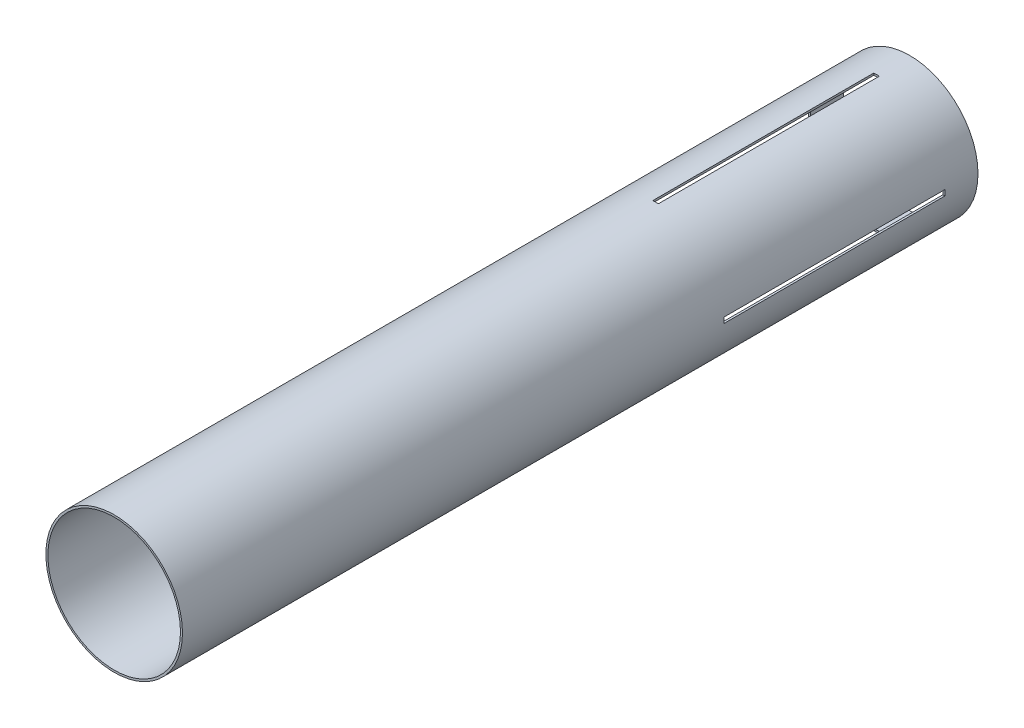
SolidWorks part; units mm, degrees
ref_plane "Front Plane" through (0, 0, 0) normal (0, 0, 1) x (1, 0, 0)
ref_plane "Top Plane" through (0, 0, 0) normal (0, 1, 0) x (1, 0, 0)
ref_plane "Right Plane" through (0, 0, 0) normal (1, 0, 0) x (0, 0, -1)
sketch "Sketch1" plane through (0, 0, 0) normal (0, 0, 1) x (1, 0, 0)
  circle A0 centre (0, 0) radius 39.2557
  circle A1 centre (0, 0) radius 38.1
  dimension "D1" = 76.2
  dimension "D2" = 78.5114
extrude "Boss-Extrude1" add sketch "Sketch1" along normal mid plane 457.2
sketch "Sketch3" plane through (0, 0, 0) normal (0, 1, 0) x (1, 0, 0)
  line L0 (39.2557, 228.6) -> (-39.2557, 228.6) construction
  line L1 (1.5875, 82.55) -> (-1.5875, 82.55)
  line L2 (1.5875, 82.55) -> (1.5875, 209.55)
  line L3 (1.5875, 209.55) -> (-1.5875, 209.55)
  line L4 (-1.5875, 82.55) -> (-1.5875, 209.55)
  line L5 (1.5875, 82.55) -> (-1.5875, 209.55) construction
  line L6 (1.5875, 209.55) -> (-1.5875, 82.55) construction
  line L7 (39.2557, 228.6) -> (-39.2557, 228.6) construction
  point P0 (0, 146.05)
  point P7 (0, 0)
  dimension "D1" = 3.175
  dimension "D2" = 127
  dimension "D3" = 19.05
extrude "Cut-Extrude1" cut sketch "Sketch3" along normal through all
pattern_circular "CirPattern1" count 4 over 360 about axis through (0, 0, 0) along (0, 0, 1) of "Cut-Extrude1"
equation "\"AIRFRAME_OD\"= 3.091in"
equation "\"AIRFRAME_ID\"= 3.00in"
equation "\"FLAT_T\" = 0.125in"
equation "\"NOSE_EXP_L\"= 3.5in"
equation "\"NOSE_SHOULDER_L\" = 5in"
equation "\"MAIN_L\" = 18in"
equation "\"RECO_COUP_L\" = 6in"
equation "\"RECO_SWITCH_L\" = 1.5in"
equation "\"DROGUE_L\" = 14in"
equation "\"ATS_FORE_COUP_L\" = 4in"
equation "\"ATS_AFT_COUP_L\" = 4in"
equation "\"LOWER_L\" = 18in"
equation "\"FIN_N\" = 4"
equation "\"CR_AFT_X\" = 0.5in"
equation "\"CR_FORE_X\" = 6in"
equation "\"D1@Sketch1\"=\"AIRFRAME_ID\""
equation "\"D2@Sketch1\"=\"AIRFRAME_OD\""
equation "\"D1@Boss-Extrude1\"=\"LOWER_L\""
equation "\"FIN_ROOT\" = 5in"
equation "\"FIN_X\" = 0.75in"
equation "\"MOTOR_OD\" = 2.25in"
equation "\"MOTOR_ID\" = 2.126in"
equation "\"D1@Sketch3\"=\"FLAT_T\""
equation "\"D2@Sketch3\"=\"FIN_ROOT\""
equation "\"D3@Sketch3\"=\"FIN_X\""
equation "\"D1@CirPattern1\"=\"FIN_N\""
